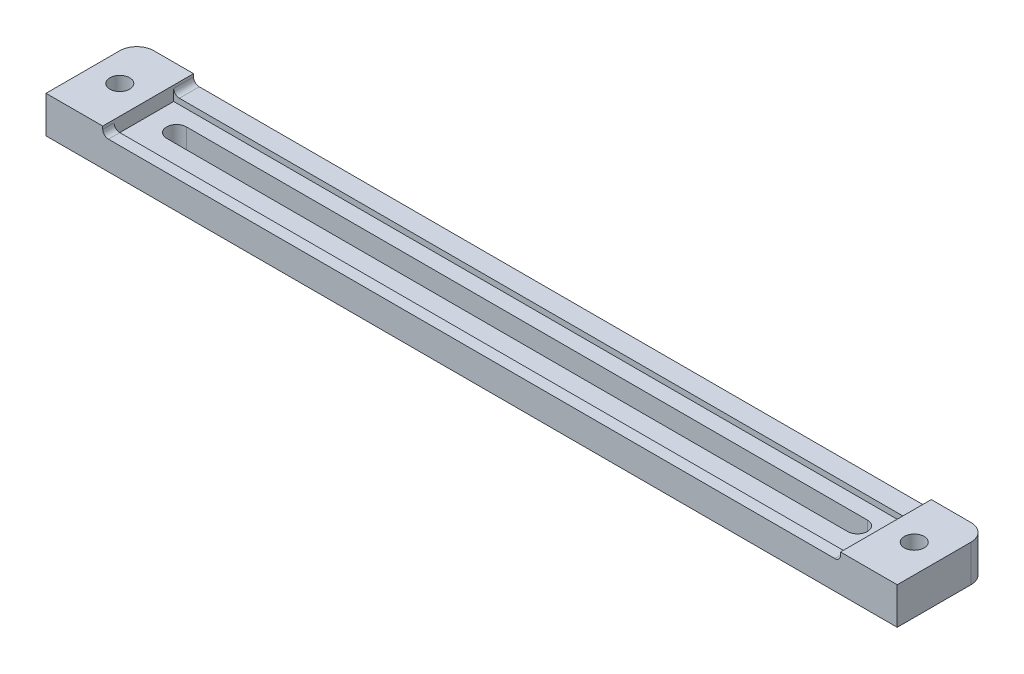
SolidWorks part; units mm, degrees
ref_plane "Front Plane" through (0, 0, 0) normal (0, 0, 1) x (1, 0, 0)
ref_plane "Top Plane" through (0, 0, 0) normal (0, 1, 0) x (1, 0, 0)
ref_plane "Right Plane" through (0, 0, 0) normal (1, 0, 0) x (0, 0, -1)
sketch "Sketch1" plane through (0, 0, 0) normal (0, 1, 0) x (1, 0, 0)
  line L0 (0, 0) -> (0, 8) construction
  line L1 (75, -8) -> (-75, -8)
  line L2 (75, -8) -> (75, 5)
  line L3 (72, 8) -> (-72, 8)
  line L4 (-75, -8) -> (-75, 5)
  line L5 (75, -8) -> (-75, 8) construction
  line L6 (75, 8) -> (-75, -8) construction
  line L8 (60, -1.75) -> (-60, -1.75)
  line L9 (60, -1.75) -> (60, 1.75)
  line L10 (60, 1.75) -> (-60, 1.75)
  line L11 (-60, -1.75) -> (-60, 1.75)
  line L12 (60, -1.75) -> (-60, 1.75) construction
  line L13 (60, 1.75) -> (-60, -1.75) construction
  circle A0 centre (-70, 0) radius 1.75
  circle A1 centre (70, 0) radius 1.75
  circle A2 centre (-60, 0) radius 1.75
  circle A3 centre (60, 0) radius 1.75
  arc A4 (72, 8) -> (75, 5) centre (72, 5) cw
  arc A5 (-72, 8) -> (-75, 5) centre (-72, 5) ccw
  point P0 (0, 0)
  dimension "D3" = 3.5
  dimension "D8" = 3
  dimension "D1" = 150
  dimension "D2" = 16
  dimension "D4" = 5
  dimension "D5" = 8
  dimension "D6" = 3.5
  dimension "D7" = 120
extrude "Boss-Extrude1" add sketch "Sketch1" along normal blind 4 contours L3 A5 L4 L1 L2 A4 L10 A3 L8 A2 A1 A0
sketch "Sketch2" plane through (0, 4, 0) normal (0, 1, 0) x (1, 0, 0)
  line L0 (-65, -8) -> (-65, 8)
  line L1 (75, -8) -> (-75, -8) construction
  line L2 (72, 8) -> (-72, 8) construction
  line L3 (65, -8) -> (65, 8)
  line L4 (75, -8) -> (75, 5) construction
  line L5 (-75, -8) -> (-75, 5) construction
  line L6 (-65, -6) -> (65, -6)
  line L7 (-65, 4.5) -> (65, 4.5)
  line L8 (75, -8) -> (65, -8)
  line L9 (-75, -8) -> (-75, 5)
  line L10 (-72, 8) -> (-65, 8)
  line L11 (-65, 8) -> (65, 8)
  line L12 (65, 8) -> (72, 8)
  line L13 (75, 5) -> (75, -8)
  line L14 (65, -8) -> (-65, -8)
  line L15 (-75, -8) -> (-65, -8)
  arc A0 (-75, 5) -> (-72, 8) centre (-72, 5) cw
  arc A1 (72, 8) -> (75, 5) centre (72, 5) cw
  circle A2 centre (70, 0) radius 1.75
  circle A3 centre (-70, 0) radius 1.75
  dimension "D1" = 10
  dimension "D2" = 10
  dimension "D3" = 2
  dimension "D4" = 10.5
extrude "Boss-Extrude2" add sketch "Sketch2" along normal blind 1
sketch "Sketch3" plane through (0, 5, 0) normal (0, 1, 0) x (1, 0, 0)
  line L0 (65, 4.5) -> (65, 8)
  line L1 (72, 8) -> (-72, 8) construction
  line L2 (65, -6) -> (65, -8)
  line L3 (-75, -8) -> (75, -8) construction
  line L4 (65, -8) -> (75, -8)
  line L5 (75, -8) -> (75, 5)
  line L6 (72, 8) -> (65, 8)
  line L7 (65, 4.5) -> (65, -6)
  line L8 (-65, 4.5) -> (-65, 8)
  line L9 (-65, 8) -> (-72, 8)
  line L10 (-75, 5) -> (-75, -8)
  line L11 (-75, -8) -> (-65, -8)
  line L12 (-65, -8) -> (-65, -6)
  line L13 (-65, -6) -> (-65, 4.5)
  arc A0 (75, 5) -> (72, 8) centre (72, 5) ccw
  arc A1 (-72, 8) -> (-75, 5) centre (-72, 5) ccw
  circle A2 centre (-70, 0) radius 1.75
  circle A3 centre (70, 0) radius 1.75
extrude "Boss-Extrude3" add sketch "Sketch3" along normal blind 1.5
fillet "Fillet1" radius 1 4 edges at (65, 5, -6.25) (65, 5, 7) (-65, 5, -6.25) (-65, 5, 7)
